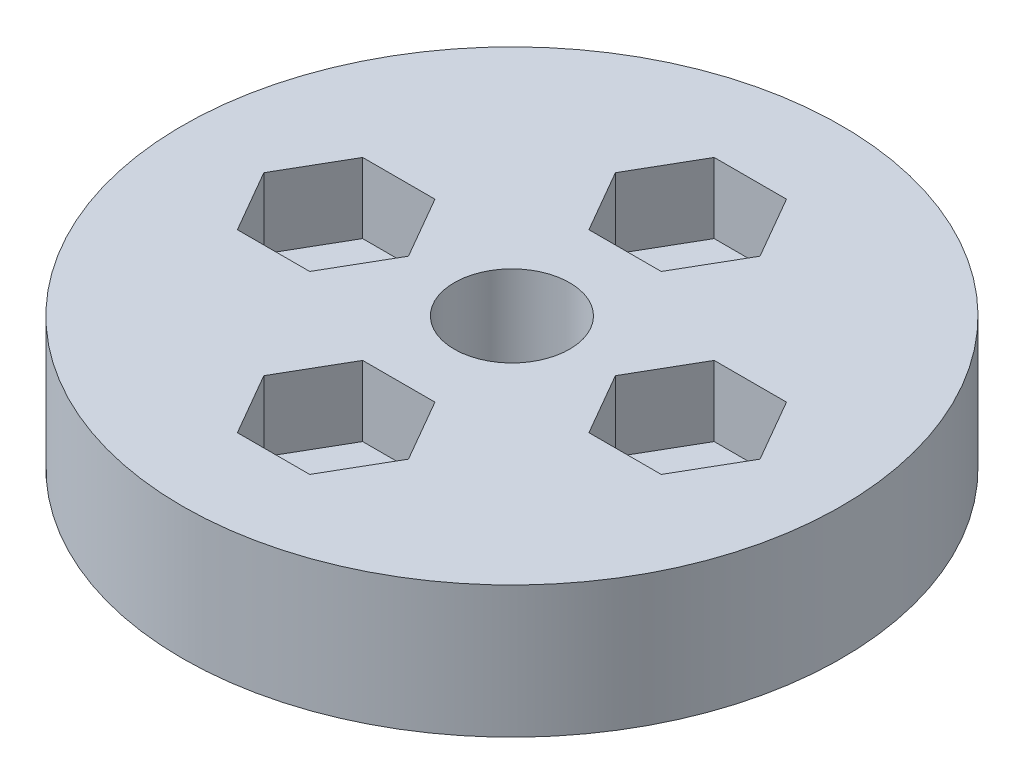
SolidWorks part; units mm, degrees
ref_plane "Front Plane" through (0, 0, 0) normal (0, 0, 1) x (1, 0, 0)
ref_plane "Top Plane" through (0, 0, 0) normal (0, 1, 0) x (1, 0, 0)
ref_plane "Right Plane" through (0, 0, 0) normal (1, 0, 0) x (0, 0, -1)
sketch "Sketch1" plane through (0, 0, 0) normal (0, 1, 0) x (1, 0, 0)
  circle A0 centre (0, 0) radius 8 construction
  circle A1 centre (0, 0) radius 15
  circle A2 centre (0, 8) radius 1.5
  circle A3 centre (8, 0) radius 1.5
  circle A4 centre (0, -8) radius 1.5
  circle A5 centre (-8, 0) radius 1.5
  circle A6 centre (0, 0) radius 2.625
  point P15 (0, 0)
  dimension "D1" = 16
  dimension "D2" = 3
  dimension "D4" = 30
  dimension "D5" = 5.25
  dimension "D3" = 4
extrude "Boss-Extrude1" add sketch "Sketch1" along normal blind 6
sketch "Sketch2" plane through (0, 6, 0) normal (0, 1, 0) x (1, 0, 0)
  line L1 (3.2909, 8) -> (1.6454, 10.85)
  line L2 (1.6454, 10.85) -> (-1.6454, 10.85)
  line L3 (-1.6454, 10.85) -> (-3.2909, 8)
  line L4 (-3.2909, 8) -> (-1.6454, 5.15)
  line L5 (-1.6454, 5.15) -> (1.6454, 5.15)
  line L6 (1.6454, 5.15) -> (3.2909, 8)
  line L7 (11.2909, 0) -> (9.6454, 2.85)
  line L8 (9.6454, 2.85) -> (6.3546, 2.85)
  line L9 (6.3546, 2.85) -> (4.7091, 0)
  line L10 (4.7091, 0) -> (6.3546, -2.85)
  line L11 (6.3546, -2.85) -> (9.6454, -2.85)
  line L12 (9.6454, -2.85) -> (11.2909, 0)
  line L13 (-4.7091, 0) -> (-6.3546, 2.85)
  line L14 (-6.3546, 2.85) -> (-9.6454, 2.85)
  line L15 (-9.6454, 2.85) -> (-11.2909, 0)
  line L16 (-11.2909, 0) -> (-9.6454, -2.85)
  line L17 (-9.6454, -2.85) -> (-6.3546, -2.85)
  line L18 (-6.3546, -2.85) -> (-4.7091, 0)
  line L19 (3.2909, -8) -> (1.6454, -5.15)
  line L20 (1.6454, -5.15) -> (-1.6454, -5.15)
  line L21 (-1.6454, -5.15) -> (-3.2909, -8)
  line L22 (-3.2909, -8) -> (-1.6454, -10.85)
  line L23 (-1.6454, -10.85) -> (1.6454, -10.85)
  line L24 (1.6454, -10.85) -> (3.2909, -8)
  circle A0 centre (0, 8) radius 2.85 construction
  circle A1 centre (8, 0) radius 2.85 construction
  circle A2 centre (-8, 0) radius 2.85 construction
  circle A3 centre (0, -8) radius 2.85 construction
  point P28 (0, -5.15)
  dimension "D1" = 5.7
  dimension "D2" = 5.7
  dimension "D3" = 5.7
  dimension "D4" = 5.7
extrude "Cut-Extrude1" cut sketch "Sketch2" against normal blind 3.2
